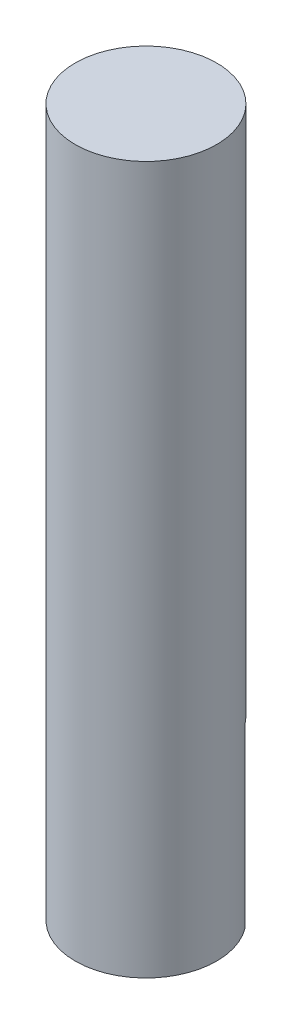
SolidWorks part; units mm, degrees
ref_plane "Front Plane" through (0, 0, 0) normal (0, 0, 1) x (1, 0, 0)
ref_plane "Top Plane" through (0, 0, 0) normal (0, 1, 0) x (1, 0, 0)
ref_plane "Right Plane" through (0, 0, 0) normal (1, 0, 0) x (0, 0, -1)
sketch "Sketch2" plane through (0, 0, 0) normal (0, 1, 0) x (1, 0, 0)
  circle A0 centre (0, 0) radius 5
  dimension "D1" = 10
extrude "Boss-Extrude1" add sketch "Sketch2" along normal blind 50
sketch "Sketch3" plane through (0, 0, 0) normal (0, 1, 0) x (1, 0, 0)
  line L0 (-4, 3) -> (4, 3)
  circle A0 centre (0, 0) radius 5 construction
  arc A1 (-4, 3) -> (4, 3) centre (0, 0) cw
  dimension "D2" = 5
  dimension "D1" = 3
extrude "Cut-Extrude1" cut sketch "Sketch3" along normal blind 12.5
